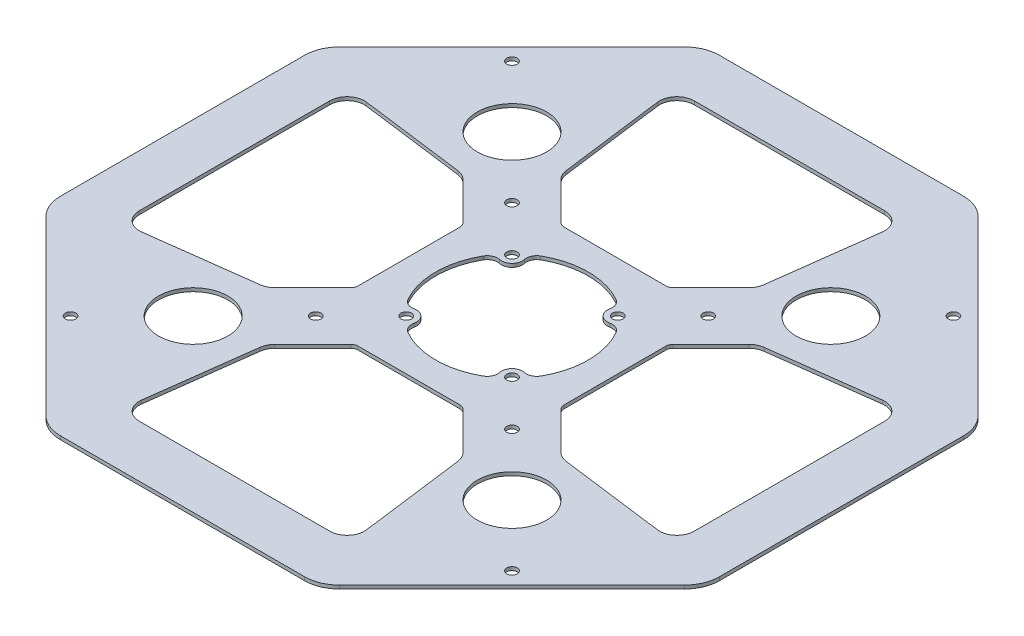
SolidWorks part; units mm, degrees
material "Hexcel AS4C (3000 Filaments)"
ref_plane "Front Plane" through (0, 0, 0) normal (0, 0, 1) x (1, 0, 0)
ref_plane "Top Plane" through (0, 0, 0) normal (0, 1, 0) x (1, 0, 0)
ref_plane "Right Plane" through (0, 0, 0) normal (1, 0, 0) x (0, 0, -1)
sketch "Sketch1" plane through (0, 0, 0) normal (0, 1, 0) x (1, 0, 0)
  line L22 (27.0793, 41.2214) -> (16.1421, 30.2843)
  line L24 (30.2843, 16.1421) -> (41.2214, 27.0793)
  line L26 (41.2214, -27.0793) -> (30.2843, -16.1421)
  line L27 (16.1421, -30.2843) -> (27.0793, -41.2214)
  line L30 (-27.0793, -41.2214) -> (-16.1421, -30.2843)
  line L31 (-30.2843, -16.1421) -> (-41.2214, -27.0793)
  line L34 (-41.2214, 27.0793) -> (-30.2843, 16.1421)
  line L35 (-16.1421, 30.2843) -> (-27.0793, 41.2214)
  line L36 (32.4086, 74.3595) -> (28.5026, 44.1165)
  line L38 (-14.7279, 29.6985) -> (14.7279, 29.6985)
  line L39 (29.6985, 14.7279) -> (29.6985, -14.7279)
  line L40 (14.7279, -29.6985) -> (-14.7279, -29.6985)
  line L41 (-29.6985, -14.7279) -> (-29.6985, 14.7279)
  line L42 (92.0711, 42.2792) -> (42.2792, 92.0711)
  line L52 (27.4498, 80) -> (-27.4498, 80)
  line L54 (-80, 27.4498) -> (-80, -27.4498)
  line L56 (-27.4498, -80) -> (27.4498, -80)
  line L58 (80, -27.4498) -> (80, 27.4498)
  line L59 (44.1165, 28.5026) -> (74.3595, 32.4086)
  line L60 (74.3595, -32.4086) -> (44.1165, -28.5026)
  line L61 (28.5026, -44.1165) -> (32.4086, -74.3595)
  line L62 (-32.4086, -74.3595) -> (-28.5026, -44.1165)
  line L63 (-44.1165, -28.5026) -> (-74.3595, -32.4086)
  line L64 (-74.3595, 32.4086) -> (-44.1165, 28.5026)
  line L65 (-28.5026, 44.1165) -> (-32.4086, 74.3595)
  line L66 (80, 33.1371) -> (33.1371, 80) [skipped]
  line L67 (33.1371, -80) -> (80, -33.1371) [skipped]
  line L68 (-80, -33.1371) -> (-33.1371, -80) [skipped]
  line L69 (-33.1371, 80) -> (-80, 33.1371) [skipped]
  line L70 (42.4264, 28.2843) -> (28.2843, 42.4264) [skipped]
  line L71 (35.2082, 95) -> (-35.2082, 95)
  line L72 (-92.0711, 42.2792) -> (-42.2792, 92.0711)
  line L73 (-95, 35.2082) -> (-95, -35.2082)
  line L74 (15.5563, 26.8701) -> (26.8701, 15.5563) [skipped]
  line L75 (-92.0711, -42.2792) -> (-42.2792, -92.0711)
  line L76 (-35.2082, -95) -> (35.2082, -95)
  line L77 (42.2792, -92.0711) -> (92.0711, -42.2792)
  line L78 (95, -35.2082) -> (95, 35.2082)
  arc A0 (-27.0793, -41.2214) -> (-28.5026, -44.1165) centre (-23.5437, -44.7569) ccw
  circle A1 centre (63.6396, 63.6396) radius 1.5
  circle A2 centre (28.2843, 28.2843) radius 1.5
  circle A3 centre (63.6396, -63.6396) radius 1.5
  circle A4 centre (28.2843, -28.2843) radius 1.5
  circle A5 centre (-63.6396, -63.6396) radius 1.5
  circle A6 centre (-28.2843, -28.2843) radius 1.5
  circle A7 centre (-63.6396, 63.6396) radius 1.5
  circle A8 centre (-28.2843, 28.2843) radius 1.5
  arc A9 (-32.4086, -74.3595) -> (-27.4498, -80) centre (-27.4498, -75) ccw
  arc A10 (27.4498, -80) -> (32.4086, -74.3595) centre (27.4498, -75) ccw
  arc A11 (28.5026, -44.1165) -> (27.0793, -41.2214) centre (23.5437, -44.7569) ccw
  arc A12 (41.2214, -27.0793) -> (44.1165, -28.5026) centre (44.7569, -23.5437) ccw
  arc A13 (74.3595, -32.4086) -> (80, -27.4498) centre (75, -27.4498) ccw
  arc A14 (80, 27.4498) -> (74.3595, 32.4086) centre (75, 27.4498) ccw
  arc A15 (44.1165, 28.5026) -> (41.2214, 27.0793) centre (44.7569, 23.5437) ccw
  arc A16 (27.0793, 41.2214) -> (28.5026, 44.1165) centre (23.5437, 44.7569) ccw
  arc A17 (-28.5026, 44.1165) -> (-27.0793, 41.2214) centre (-23.5437, 44.7569) ccw
  arc A18 (32.4086, 74.3595) -> (27.4498, 80) centre (27.4498, 75) ccw
  arc A19 (-27.4498, 80) -> (-32.4086, 74.3595) centre (-27.4498, 75) ccw
  arc A20 (-41.2214, 27.0793) -> (-44.1165, 28.5026) centre (-44.7569, 23.5437) ccw
  arc A21 (-41.2214, -27.0793) -> (-44.1165, -28.5026) centre (-44.7569, -23.5437) cw
  arc A22 (-74.3595, -32.4086) -> (-80, -27.4498) centre (-75, -27.4498) cw
  arc A23 (-80, 27.4498) -> (-74.3595, 32.4086) centre (-75, 27.4498) cw
  circle A32 centre (-45.9619, 45.9619) radius 10
  circle A33 centre (45.9619, 45.9619) radius 10
  circle A34 centre (45.9619, -45.9619) radius 10
  circle A35 centre (-45.9619, -45.9619) radius 10
  arc A37 (-16.1421, 30.2843) -> (-14.7279, 29.6985) centre (-14.7279, 31.6985) ccw
  arc A38 (14.7279, 29.6985) -> (16.1421, 30.2843) centre (14.7279, 31.6985) ccw
  arc A39 (29.6985, 14.7279) -> (30.2843, 16.1421) centre (31.6985, 14.7279) cw
  arc A40 (29.6985, -14.7279) -> (30.2843, -16.1421) centre (31.6985, -14.7279) ccw
  arc A41 (16.1421, -30.2843) -> (14.7279, -29.6985) centre (14.7279, -31.6985) ccw
  arc A42 (-14.7279, -29.6985) -> (-16.1421, -30.2843) centre (-14.7279, -31.6985) ccw
  arc A43 (-30.2843, -16.1421) -> (-29.6985, -14.7279) centre (-31.6985, -14.7279) ccw
  arc A44 (-29.6985, 14.7279) -> (-30.2843, 16.1421) centre (-31.6985, 14.7279) ccw
  arc A53 (-95, -35.2082) -> (-92.0711, -42.2792) centre (-85, -35.2082) ccw
  arc A54 (-42.2792, -92.0711) -> (-35.2082, -95) centre (-35.2082, -85) ccw
  arc A55 (35.2082, -95) -> (42.2792, -92.0711) centre (35.2082, -85) ccw
  arc A56 (92.0711, -42.2792) -> (95, -35.2082) centre (85, -35.2082) ccw
  arc A57 (95, 35.2082) -> (92.0711, 42.2792) centre (85, 35.2082) ccw
  arc A58 (42.2792, 92.0711) -> (35.2082, 95) centre (35.2082, 85) ccw
  arc A59 (-35.2082, 95) -> (-42.2792, 92.0711) centre (-35.2082, 85) ccw
  arc A60 (-92.0711, 42.2792) -> (-95, 35.2082) centre (-85, 35.2082) ccw
  arc A61 (22, 0) -> (19.1282, -10.8679) centre (0, 0) cw
  circle A62 centre (15.25, 15.25) radius 1.5
  arc A64 (0, 22) -> (10.8679, 19.1282) centre (0, 0) cw
  arc A65 (12.318, 15.8849) -> (15.8849, 12.318) centre (15.25, 15.25) ccw
  arc A66 (19.1282, 10.8679) -> (22, 0) centre (0, 0) cw
  arc A67 (15.8849, -12.318) -> (12.318, -15.8849) centre (15.25, -15.25) ccw
  circle A68 centre (15.25, -15.25) radius 1.5
  arc A69 (10.8679, -19.1282) -> (0, -22) centre (0, 0) cw
  arc A70 (0, -22) -> (-10.8679, -19.1282) centre (0, 0) cw
  arc A71 (-12.318, -15.8849) -> (-15.8849, -12.318) centre (-15.25, -15.25) ccw
  circle A72 centre (-15.25, -15.25) radius 1.5
  arc A73 (-19.1282, -10.8679) -> (-22, 0) centre (0, 0) cw
  arc A74 (-22, 0) -> (-19.1282, 10.8679) centre (0, 0) cw
  arc A75 (-15.8849, 12.318) -> (-12.318, 15.8849) centre (-15.25, 15.25) ccw
  circle A76 centre (-15.25, 15.25) radius 1.5
  arc A77 (-10.8679, 19.1282) -> (0, 22) centre (0, 0) cw
  arc A78 (-10.8679, 19.1282) -> (-12.318, 15.8849) centre (-9.3859, 16.5198) ccw
  arc A79 (-15.8849, 12.318) -> (-19.1282, 10.8679) centre (-16.5198, 9.3859) ccw
  arc A80 (-19.1282, -10.8679) -> (-15.8849, -12.318) centre (-16.5198, -9.3859) ccw
  arc A81 (-12.318, -15.8849) -> (-10.8679, -19.1282) centre (-9.3859, -16.5198) ccw
  arc A82 (10.8679, -19.1282) -> (12.318, -15.8849) centre (9.3859, -16.5198) ccw
  arc A83 (15.8849, -12.318) -> (19.1282, -10.8679) centre (16.5198, -9.3859) ccw
  arc A84 (19.1282, 10.8679) -> (15.8849, 12.318) centre (16.5198, 9.3859) ccw
  arc A85 (10.8679, 19.1282) -> (12.318, 15.8849) centre (9.3859, 16.5198) cw
  point P28 (0, 0)
  point P46 (0, 0)
  point P71 (0, 0)
  point P123 (0, 0)
  point P164 (0, 0)
  dimension "D2" = 4
  dimension "D1" = 4
  dimension "D3" = 5
  dimension "D4" = 2
  dimension "D5" = 10
  dimension "D6" = 4
  dimension "D7" = 3
  dimension "D8" = 4
extrude "Boss-Extrude1" add sketch "Sketch1" along normal blind 1
